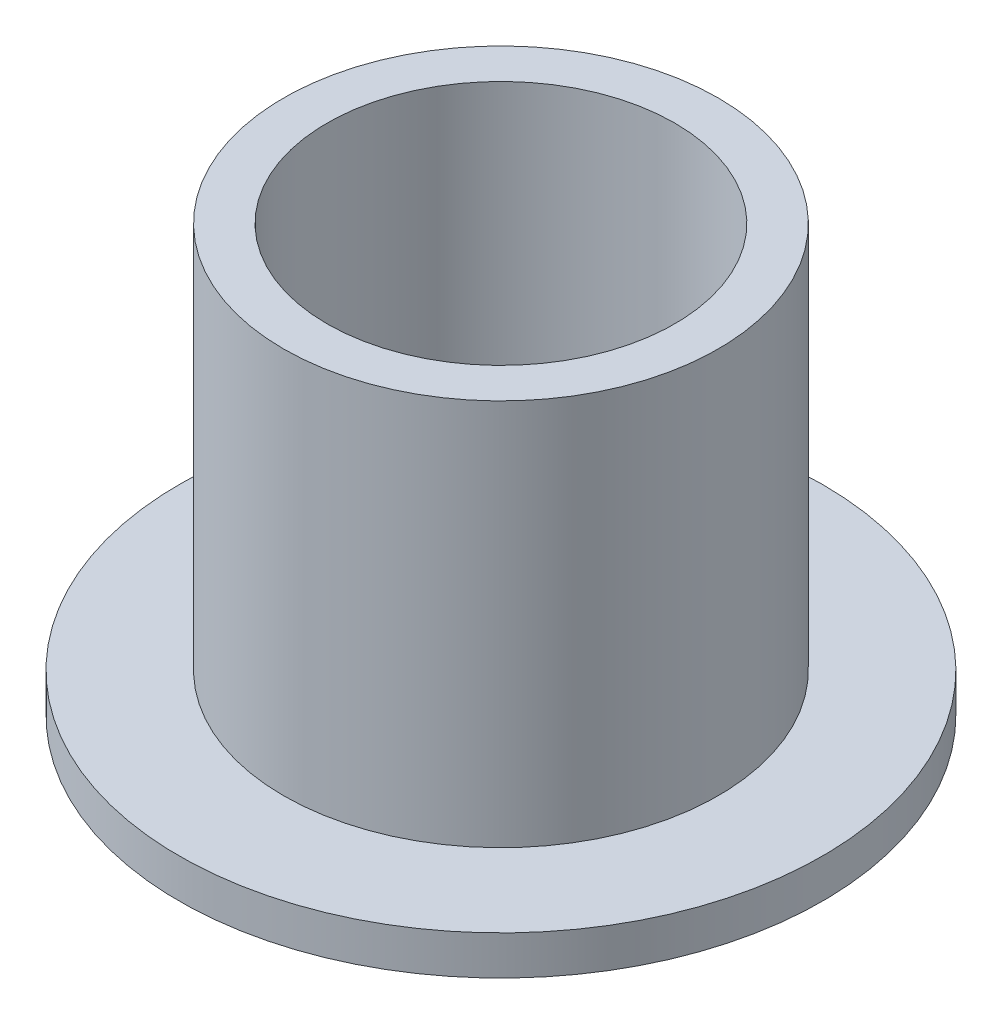
SolidWorks part; units mm, degrees
ref_plane "Front Plane" through (0, 0, 0) normal (0, 0, 1) x (1, 0, 0)
ref_plane "Top Plane" through (0, 0, 0) normal (0, 1, 0) x (1, 0, 0)
ref_plane "Right Plane" through (0, 0, 0) normal (1, 0, 0) x (0, 0, -1)
sketch "Sketch1" plane through (0, 0, 0) normal (0, 0, 1) x (1, 0, 0)
  line L0 (0, 0) -> (0, 12.4925) construction
  line L1 (-4, 0) -> (-7.4, 0)
  line L2 (-7.4, 0) -> (-7.4, 0.9)
  line L3 (-7.4, 0.9) -> (-5, 0.9)
  line L4 (-5, 0.9) -> (-5, 9.8)
  line L5 (-5, 9.8) -> (-4, 9.8)
  line L6 (-4, 9.8) -> (-4, 0)
  dimension "D1" = 8
  dimension "D2" = 9.8
  dimension "D3" = 1
  dimension "D4" = 0.9
  dimension "D5" = 14.8
revolve "Revolve1" add sketch "Sketch1" angle 360 about L0
